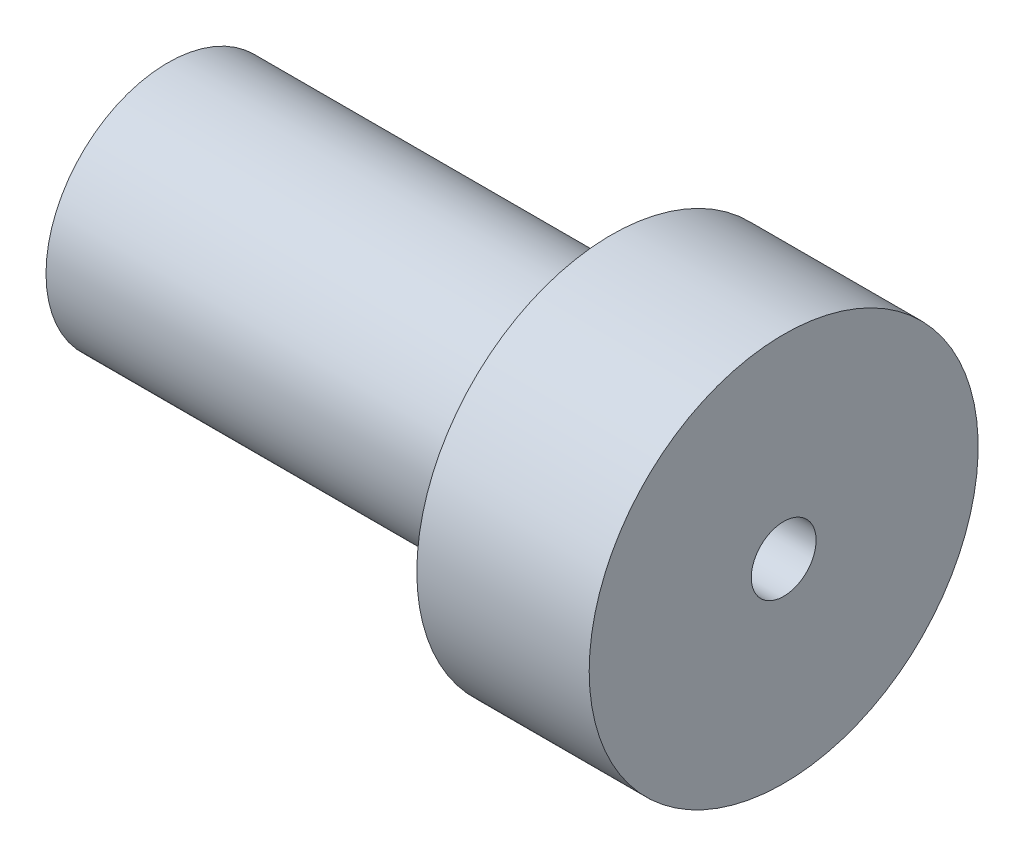
SolidWorks part; units mm, degrees
material "AISI 316 Stainless Steel Sheet (SS)"
ref_plane "Front Plane" through (0, 0, 0) normal (0, 0, 1) x (1, 0, 0)
ref_plane "Top Plane" through (0, 0, 0) normal (0, 1, 0) x (1, 0, 0)
ref_plane "Right Plane" through (0, 0, 0) normal (1, 0, 0) x (0, 0, -1)
sketch "Sketch1" plane through (0, 0, 0) normal (0, 0, 1) x (1, 0, 0)
  line L0 (0, 0) -> (0, 3.7575)
  line L1 (0, 3.7575) -> (13.6828, 3.7575)
  line L2 (13.6828, 3.7575) -> (13.6828, 6)
  line L3 (13.6828, 6) -> (19, 6)
  line L4 (19, 6) -> (19, 0)
  line L5 (19, 0) -> (0, 0)
  line L6 (0, 0) -> (-5.9552, 0) construction
  line L7 (-5.9552, 0) -> (25.4515, 0) construction
  point P11 (18.5746, 7.7276)
  dimension "D1" = 19
  dimension "D2" = 6
revolve "Revolve1" add sketch "Sketch1" angle 360 about L7
sketch "Sketch2" plane through (0, 0, 0) normal (1, 0, 0) x (0, 0, -1)
  circle A0 centre (0, 0) radius 1
  dimension "D1" = 2
extrude "Cut-Extrude2" cut sketch "Sketch2" along normal through all
